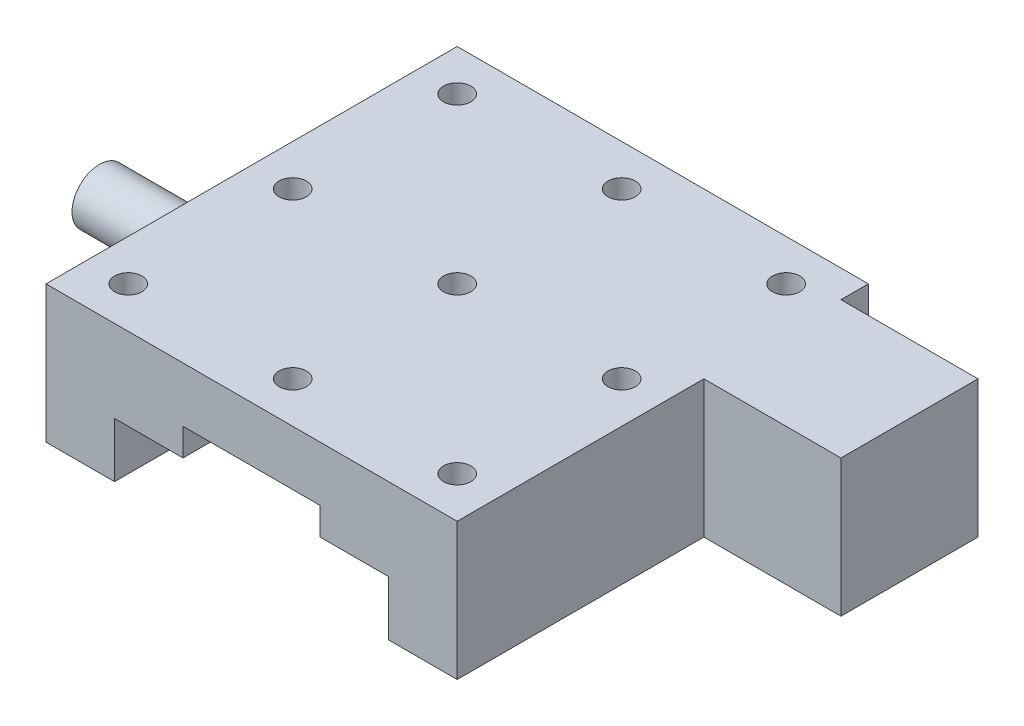
SolidWorks part; units mm, degrees
material "Простая углеродистая сталь"
ref_plane "Спереди" through (0, 0, 0) normal (0, 0, 1) x (1, 0, 0)
ref_plane "Сверху" through (0, 0, 0) normal (0, 1, 0) x (1, 0, 0)
ref_plane "Справа" through (0, 0, 0) normal (1, 0, 0) x (0, 0, -1)
sketch "Эскиз1" plane through (0, 0, 0) normal (0, 1, 0) x (1, 0, 0)
  line L0 (0, 0) -> (30, 0)
  line L1 (0, 0) -> (0, 30)
  line L2 (30, 0) -> (30, 30)
  line L3 (0, 30) -> (30, 30)
  line L4 (3, 27) -> (27, 27) construction
  line L5 (3, 27) -> (3, 3) construction
  line L6 (27, 27) -> (27, 3) construction
  line L7 (3, 3) -> (27, 3) construction
  line L8 (15, 30) -> (15, 0) construction
  line L9 (0, 15) -> (30, 15) construction
  point P8 (15, 27)
  point P12 (27, 15)
  dimension "D1" = 30
  dimension "D2" = 30
  dimension "D3" = 24
  dimension "D4" = 24
extrude "Бобышка-Вытянуть1" add sketch "Эскиз1" along normal blind 10
sketch "Эскиз2" plane through (0, 0, 0) normal (0, 0, 1) x (1, 0, 0)
  line L0 (15, 10) -> (15, 0) construction
  line L1 (0, 10) -> (30, 10) construction
  line L2 (0, 0) -> (30, 0) construction
  line L3 (5, 0) -> (5, 4)
  line L4 (5, 4) -> (10, 4)
  line L5 (10, 4) -> (10, 6)
  line L6 (10, 6) -> (20, 6)
  line L7 (5, 0) -> (25, 0)
  line L8 (25, 0) -> (25, 4)
  line L9 (25, 4) -> (20, 4)
  line L10 (20, 4) -> (20, 6)
  point P15 (15, 6)
  dimension "D1" = 10
  dimension "D2" = 4
  dimension "D3" = 2
  dimension "D4" = 5
extrude "Вырез-Вытянуть1" cut sketch "Эскиз2" against normal through all
sketch "Эскиз3" plane through (0, 10, 0) normal (0, 1, 0) x (1, 0, 0)
  line L0 (3, 27) -> (27, 27) construction
  line L1 (3, 27) -> (3, 3) construction
  line L2 (27, 27) -> (27, 3) construction
  line L3 (3, 3) -> (27, 3) construction
  line L4 (15, 30) -> (15, 0) construction
  line L5 (30, 30) -> (0, 30) construction
  line L6 (0, 0) -> (30, 0) construction
  line L7 (30, 15) -> (0, 15) construction
  line L8 (30, 0) -> (30, 30) construction
  line L9 (0, 30) -> (0, 0) construction
  circle A0 centre (3, 27) radius 1
  circle A1 centre (15, 27) radius 1
  circle A2 centre (27, 27) radius 1
  circle A3 centre (27, 15) radius 1
  circle A4 centre (27, 3) radius 1
  circle A5 centre (15, 3) radius 1
  circle A6 centre (3, 3) radius 1
  circle A7 centre (3, 15) radius 1
  circle A8 centre (15, 15) radius 1
  point P16 (27, 15)
  point P17 (15, 27)
  dimension "D3" = 2
  dimension "D1" = 24
  dimension "D2" = 24
extrude "Вырез-Вытянуть2" cut sketch "Эскиз3" against normal blind 3
sketch "Эскиз4" plane through (30, 0, 0) normal (1, 0, 0) x (0, 0, -1)
  line L0 (28, 10) -> (28, 0)
  line L1 (28, 10) -> (18, 10)
  line L2 (28, 0) -> (18, 0)
  line L3 (18, 10) -> (18, 0)
  line L4 (0, 10) -> (30, 10) construction
  line L5 (0, 0) -> (30, 0) construction
  line L6 (30, 10) -> (30, 0) construction
  dimension "D1" = 10
  dimension "D2" = 2
extrude "Бобышка-Вытянуть2" add sketch "Эскиз4" along normal blind 10
sketch "Эскиз5" plane through (0, 0, 0) normal (-1, 0, 0) x (0, 0, 1)
  line L0 (-30, 10) -> (0, 10) construction
  line L1 (0, 10) -> (0, 0) construction
  circle A0 centre (-11.5, 6) radius 1
  dimension "D1" = 2
  dimension "D3" = 11.5
  dimension "D2" = 4
extrude "Бобышка-Вытянуть3" add sketch "Эскиз5" along normal blind 1.6
sketch "Эскиз6" plane through (-1.6, 0, 0) normal (-1, 0, 0) x (0, 0, 1)
  circle A0 centre (-11.5, 6) radius 2
  circle A1 centre (-11.5, 6) radius 1
  circle A2 centre (-11.5, 6) radius 1 construction
  dimension "D2" = 4
  dimension "D1" = 0
extrude "Бобышка-Вытянуть4" add sketch "Эскиз6" along normal blind 6
